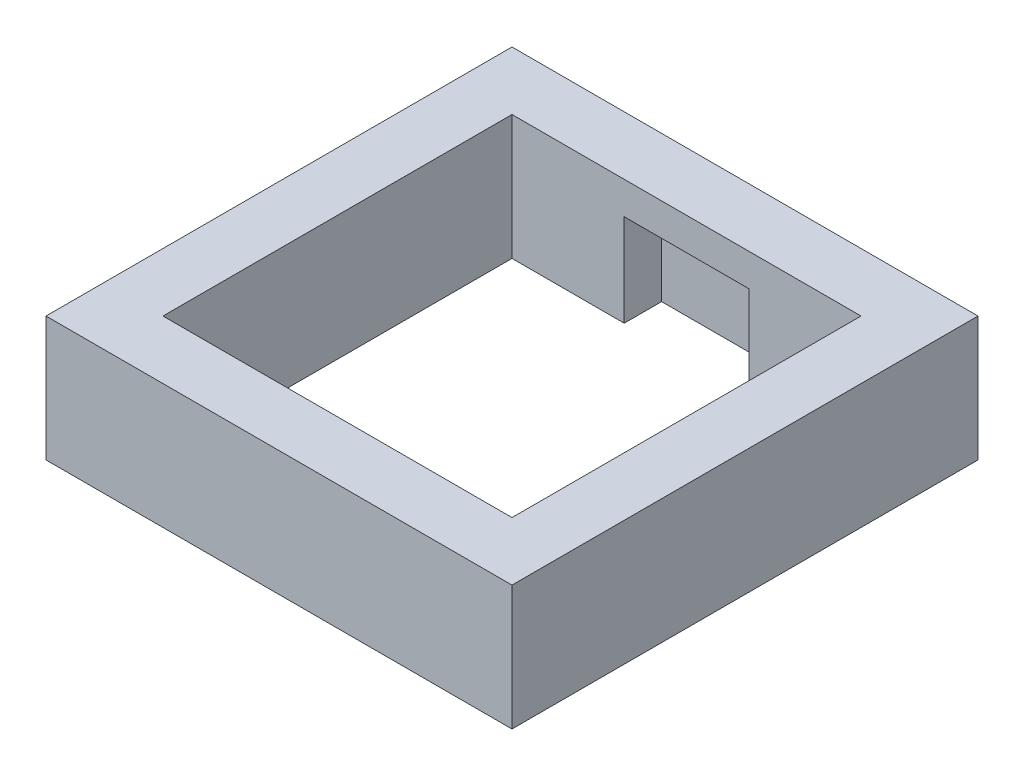
SolidWorks part; units mm, degrees
ref_plane "Front Plane" through (0, 0, 0) normal (0, 0, 1) x (1, 0, 0)
ref_plane "Top Plane" through (0, 0, 0) normal (0, 1, 0) x (1, 0, 0)
ref_plane "Right Plane" through (0, 0, 0) normal (1, 0, 0) x (0, 0, -1)
sketch "Sketch2" plane through (0, 0, 0) normal (0, 1, 0) x (1, 0, 0)
  line L0 (0, 0) -> (0, 7)
  line L1 (0, 7) -> (-2.5, 7)
  line L2 (7, 7) -> (7, -7)
  line L3 (7, -7) -> (-7, -7)
  line L4 (-7, -7) -> (-7, 7)
  line L5 (-7, 7) -> (7, 7)
  line L9 (2.5, 7) -> (-2.5, 7)
  line L10 (0, 0) -> (0, -7)
  line L11 (0, -7) -> (2.5, -7)
  line L15 (-2.5, -7) -> (2.5, -7)
  line L16 (-7, -7) -> (-9.3457, -9.3457)
  line L17 (-9.3457, 9.3457) -> (-9.3457, -9.3457)
  line L18 (7, -7) -> (9.3457, -9.3457)
  line L19 (9.3457, -9.3457) -> (-9.3457, -9.3457)
  line L20 (-7, 7) -> (-9.3457, 9.3457)
  line L21 (9.3457, -9.3457) -> (9.3457, 9.3457)
  line L22 (9.3457, 9.3457) -> (7, 7)
  line L23 (-9.3457, 9.3457) -> (9.3457, 9.3457)
  line L24 (0, -7) -> (-2.5, -7)
  line L25 (-2.5, -7) -> (-2.5, -8.5)
  line L26 (-2.5, -8.5) -> (2.5, -8.5)
  line L27 (2.5, -8.5) -> (2.5, -7)
  line L28 (0, 7) -> (-2.5, 7)
  line L29 (-2.5, 7) -> (-2.5, 8.5)
  line L30 (-2.5, 8.5) -> (2.5, 8.5)
  line L31 (2.5, 8.5) -> (2.5, 7)
extrude "Boss-Extrude2" add sketch "Sketch2" along normal blind 5 contours L4 L20 L17 L16 | L30 L31 L5 L22 L23 L20 L29 | L31 L30 L29 L1 L5 | L21 L22 L2 L18 | L27 L26 L25 L3 L16 L19 L18 | L26 L27 L3 L25
sketch "Sketch3" plane through (0, 0, 0) normal (0, -1, 0) x (1, 0, 0)
  line L0 (0, 0) -> (0, -7)
  line L1 (-7, -7) -> (7, -7) construction
  line L2 (0, -7) -> (2.5, -7)
  line L3 (2.5, -7) -> (2.5, -8.5)
  line L4 (2.5, -8.5) -> (-2.5, -8.5)
  line L5 (-2.5, -8.5) -> (-2.5, -7)
  line L6 (-2.5, -7) -> (0, -7)
  line L7 (0, 0) -> (0, 7)
  line L8 (7, 7) -> (-7, 7) construction
  line L9 (0, 7) -> (2.5, 7)
  line L10 (2.5, 7) -> (2.5, 8.5)
  line L11 (2.5, 8.5) -> (-2.5, 8.5)
  line L12 (-2.5, 8.5) -> (-2.5, 7)
  line L13 (-2.5, 7) -> (0, 7)
  line M1 (7, -7) -> (-7, -7)
  line M3 (-7, 7) -> (7, 7)
extrude "Cut-Extrude1" cut sketch "Sketch3" against normal blind 3.7 contours L5 L4 L3 M1 | L11 L12 L10 M3
